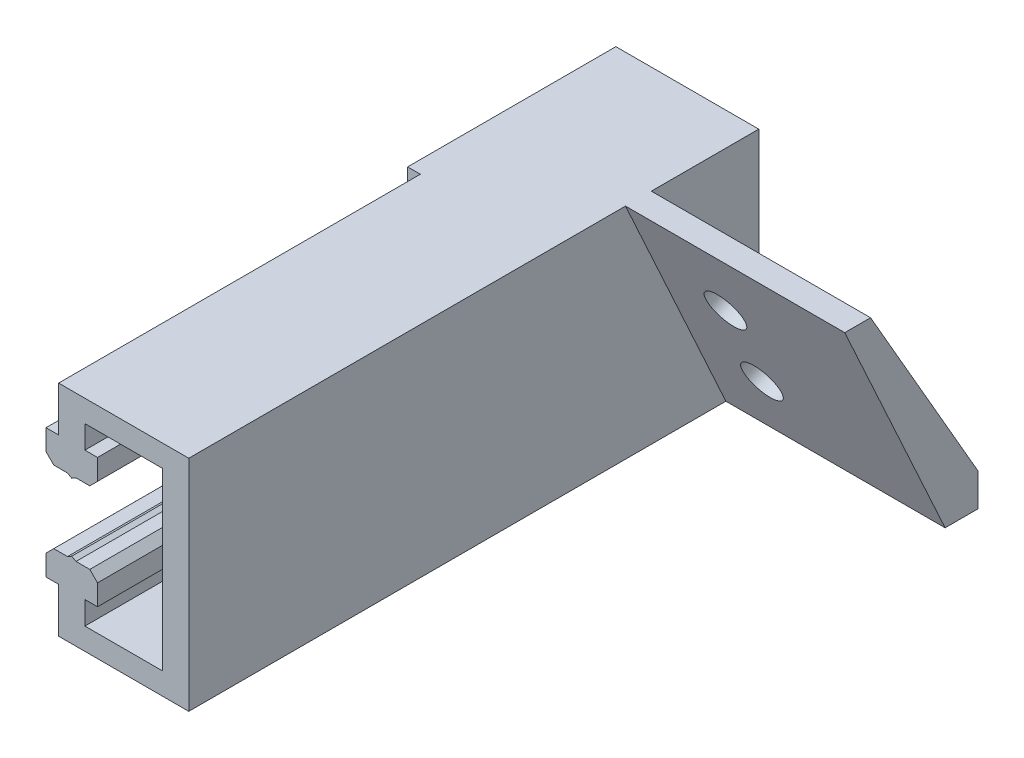
SolidWorks part; units mm, degrees
ref_plane "Front Plane" through (0, 0, 0) normal (0, 0, 1) x (1, 0, 0)
ref_plane "Top Plane" through (0, 0, 0) normal (0, 1, 0) x (1, 0, 0)
ref_plane "Right Plane" through (0, 0, 0) normal (1, 0, 0) x (0, 0, -1)
sketch "Sketch3" plane through (0, 0, 0) normal (0, 0, 1) x (1, 0, 0)
  line L0 (1253.633, 553.9424) -> (1265.5081, 553.9424)
  line L1 (1265.5081, 553.9424) -> (1265.5081, 533.9424)
  line L2 (1265.5081, 533.9424) -> (1253.633, 533.9424)
  line L3 (1253.633, 533.9424) -> (1253.633, 538.0424)
  line L4 (1253.633, 538.0424) -> (1252.483, 538.0424)
  line L5 (1252.483, 538.0424) -> (1252.483, 539.9353)
  line L6 (1252.483, 539.9353) -> (1253.1902, 540.6424)
  line L7 (1253.1902, 540.6424) -> (1254.4475, 540.6424)
  line L8 (1254.4475, 540.6424) -> (1254.8331, 540.8651)
  line L9 (1254.8331, 540.8651) -> (1255.2187, 540.6424)
  line L10 (1255.2187, 540.6424) -> (1256.4759, 540.6424)
  line L11 (1256.4759, 540.6424) -> (1257.1831, 539.9353)
  line L12 (1257.1831, 539.9353) -> (1257.1831, 538.0424)
  line L13 (1257.1831, 538.0424) -> (1256.0331, 538.0424)
  line L14 (1256.0331, 538.0424) -> (1256.0331, 535.9424)
  line L15 (1256.0331, 535.9424) -> (1263.1269, 535.9424)
  line L16 (1263.1269, 535.9424) -> (1263.1269, 551.9424)
  line L17 (1263.1269, 551.9424) -> (1256.0331, 551.9424)
  line L18 (1256.0331, 551.9424) -> (1256.0331, 549.8424)
  line L19 (1256.0331, 549.8424) -> (1257.1831, 549.8424)
  line L20 (1257.1831, 549.8424) -> (1257.1831, 547.9495)
  line L21 (1257.1831, 547.9495) -> (1256.4759, 547.2424)
  line L22 (1256.4759, 547.2424) -> (1255.2187, 547.2424)
  line L23 (1255.2187, 547.2424) -> (1254.8331, 547.0197)
  line L24 (1254.8331, 547.0197) -> (1254.4475, 547.2424)
  line L25 (1254.4475, 547.2424) -> (1253.1902, 547.2424)
  line L26 (1253.1902, 547.2424) -> (1252.483, 547.9495)
  line L27 (1252.483, 547.9495) -> (1252.483, 549.8424)
  line L28 (1252.483, 549.8424) -> (1253.633, 549.8424)
  line L29 (1253.633, 549.8424) -> (1253.633, 553.9424)
extrude "Boss-Extrude1" add sketch "Sketch3" along normal blind 33
sketch "Sketch4" plane through (0, 0, 0) normal (0, 0, -1) x (-1, 0, 0)
  line L0 (-1265.5081, 533.9424) -> (-1265.5081, 553.9424)
  line L1 (-1265.5081, 533.9424) -> (-1252.4731, 533.9424)
  line L2 (-1265.5081, 553.9424) -> (-1252.4731, 553.9424)
  line L3 (-1252.4731, 533.9424) -> (-1252.4731, 553.9424)
extrude "Boss-Extrude2" add sketch "Sketch4" along normal blind 19
sketch "Sketch5" plane through (1265.5081, 0, 0) normal (1, 0, 0) x (0, 0, -1)
  line L0 (19, 533.9424) -> (16, 533.9424)
  line L1 (-33, 533.9424) -> (19, 533.9424) construction
  line L2 (19, 533.9424) -> (19, 536.9424)
  line L3 (19, 553.9424) -> (19, 533.9424) construction
  line L4 (6.842, 553.9424) -> (9.1993, 553.9424)
  line L5 (-33, 553.9424) -> (19, 553.9424) construction
  line L6 (6.842, 553.9424) -> (16, 533.9424)
  line L7 (9.1993, 553.9424) -> (19, 536.9424)
extrude "Boss-Extrude3" add sketch "Sketch5" along normal blind 20
sketch "Sketch6" plane through (0, 98.6043, -215.3408) normal (0, -0.4163, 0.9092) x (1, 0, 0)
  line L0 (1265.5081, 500.8038) -> (1265.5081, 478.8069) construction
  circle A0 centre (1271.5081, 485.3154) radius 1.8
  circle A1 centre (1271.5081, 493.3154) radius 1.8
  dimension "D1" = 6
  dimension "D2" = 6
  dimension "D3" = 8
extrude "Cut-Extrude1" cut sketch "Sketch6" against normal up to surface (3.6735 mm away)
